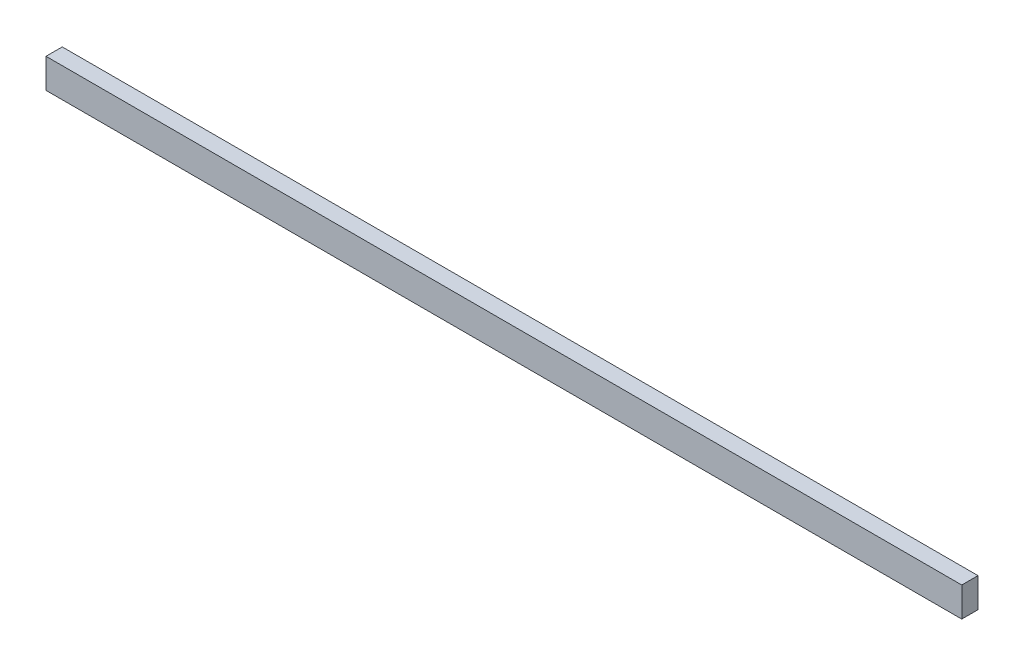
SolidWorks part; units mm, degrees
ref_plane "Plan de face" through (0, 0, 0) normal (0, 0, 1) x (1, 0, 0)
ref_plane "Plan de dessus" through (0, 0, 0) normal (0, 1, 0) x (1, 0, 0)
ref_plane "Plan de droite" through (0, 0, 0) normal (1, 0, 0) x (0, 0, -1)
sketch "Esquisse1" plane through (0, 0, 0) normal (0, 0, 1) x (1, 0, 0)
  line L1 (0, 0) -> (-310, 0)
  line L2 (0, 0) -> (0, 10)
  line L3 (0, 10) -> (-310, 10)
  line L4 (-310, 0) -> (-310, 10)
  dimension "D1" = 10
  dimension "D2" = 310
extrude "Boss.-Extru.1" add sketch "Esquisse1" along normal blind 5.5
